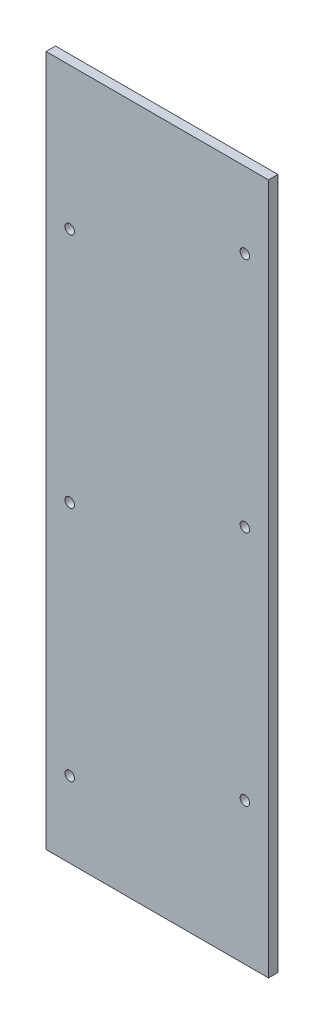
SolidWorks part; units mm, degrees
ref_plane "Front Plane" through (0, 0, 0) normal (0, 0, 1) x (1, 0, 0)
ref_plane "Top Plane" through (0, 0, 0) normal (0, 1, 0) x (1, 0, 0)
ref_plane "Right Plane" through (0, 0, 0) normal (1, 0, 0) x (0, 0, -1)
sketch "Sketch1" plane through (0, 0, 0) normal (0, 0, 1) x (1, 0, 0)
  line L1 (-47, -146) -> (47, -146)
  line L2 (-47, -146) -> (-47, 146)
  line L3 (-47, 146) -> (47, 146)
  line L4 (47, -146) -> (47, 146)
  line L5 (-47, -146) -> (47, 146) construction
  line L6 (-47, 146) -> (47, -146) construction
  point P0 (0, 0)
  dimension "D1" = 292
  dimension "D2" = 94
extrude "Boss-Extrude1" add sketch "Sketch1" along normal blind 4
sketch "Sketch2" plane through (0, 0, 4) normal (0, 0, 1) x (1, 0, 0)
  line L0 (-27, 146) -> (-27, -146) construction
  line L1 (27, -146) -> (27, 146) construction
  line L2 (-47, 146) -> (-27, 146) construction
  line L3 (-37, 146) -> (-37, -146) construction
  line L4 (47, -146) -> (47, 146)
  line L5 (47, 146) -> (-47, 146)
  line L6 (-47, 146) -> (-47, -146)
  line L7 (-47, -146) -> (47, -146)
  line L8 (47, -146) -> (47, 146) construction
  line L9 (47, 146) -> (-47, 146) construction
  line L10 (-47, 146) -> (-47, -146) construction
  line L11 (-47, -146) -> (47, -146) construction
  line L12 (27, 146) -> (47, 146) construction
  line L13 (47, 146) -> (27, 146)
  line L14 (37, 146) -> (37, -146) construction
  circle A0 centre (-37, -14) radius 2
  circle A1 centre (-37, 86) radius 2
  circle A2 centre (-37, -114) radius 2
  circle A3 centre (37, -86) radius 2
  circle A4 centre (37, 14) radius 2
  circle A5 centre (37, 114) radius 2
  dimension "D4" = 4
  dimension "D5" = 4
  dimension "D7" = 4
  dimension "D9" = 4
  dimension "D10" = 4
  dimension "D11" = 4
  dimension "D3" = 100
  dimension "D6" = 100
  dimension "D8" = 60
  dimension "D12" = 60
  dimension "D13" = 100
  dimension "D14" = 100
  dimension "D1" = 0
  dimension "D2" = 20
extrude "Cut-Extrude1" cut sketch "Sketch2" against normal blind 4 contours A2 | A3 | A4 | A0 | A1 | A5
